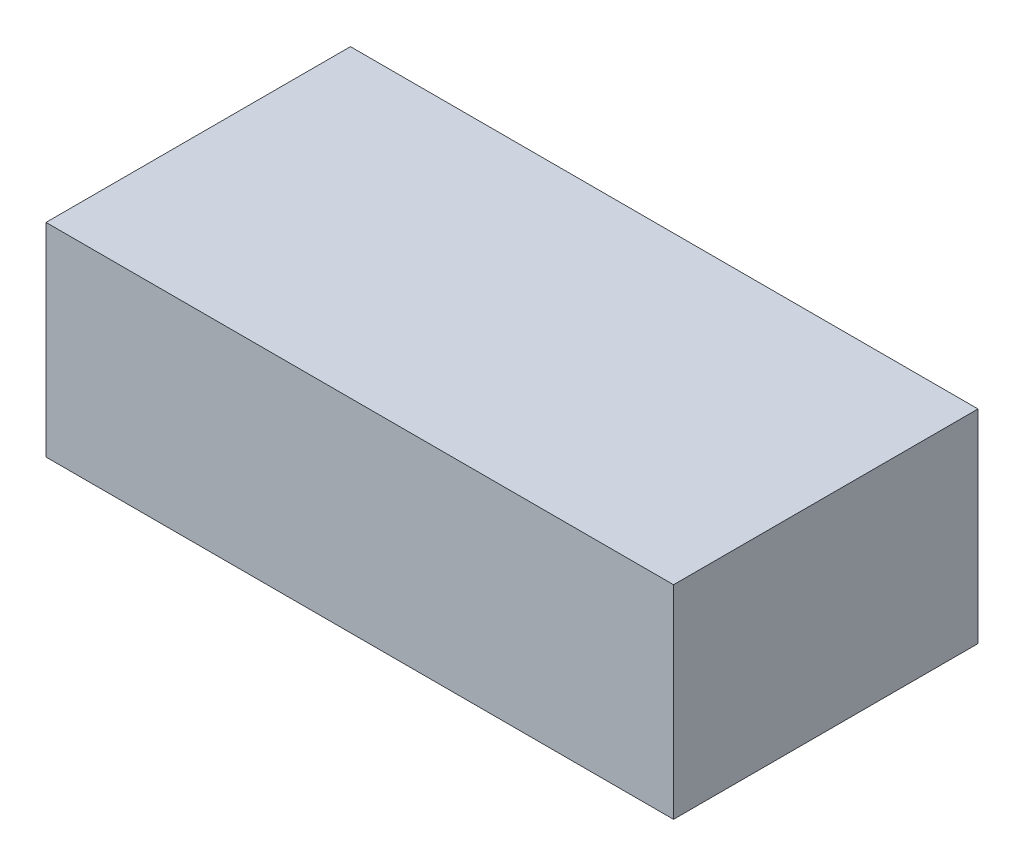
SolidWorks part; units mm, degrees
ref_plane "정면" through (0, 0, 0) normal (0, 0, 1) x (1, 0, 0)
ref_plane "윗면" through (0, 0, 0) normal (0, 1, 0) x (1, 0, 0)
ref_plane "우측면" through (0, 0, 0) normal (1, 0, 0) x (0, 0, -1)
sketch "스케치1" plane through (0, 0, 0) normal (0, 1, 0) x (1, 0, 0)
  line L1 (-24.55, -11.91) -> (24.55, -11.91)
  line L2 (-24.55, -11.91) -> (-24.55, 11.91)
  line L3 (-24.55, 11.91) -> (24.55, 11.91)
  line L4 (24.55, -11.91) -> (24.55, 11.91)
  line L5 (-24.55, -11.91) -> (24.55, 11.91) construction
  line L6 (-24.55, 11.91) -> (24.55, -11.91) construction
  point P0 (0, 0)
  dimension "D1" = 49.1
  dimension "D2" = 23.82
extrude "보스-돌출1" add sketch "스케치1" along normal blind 15.9
